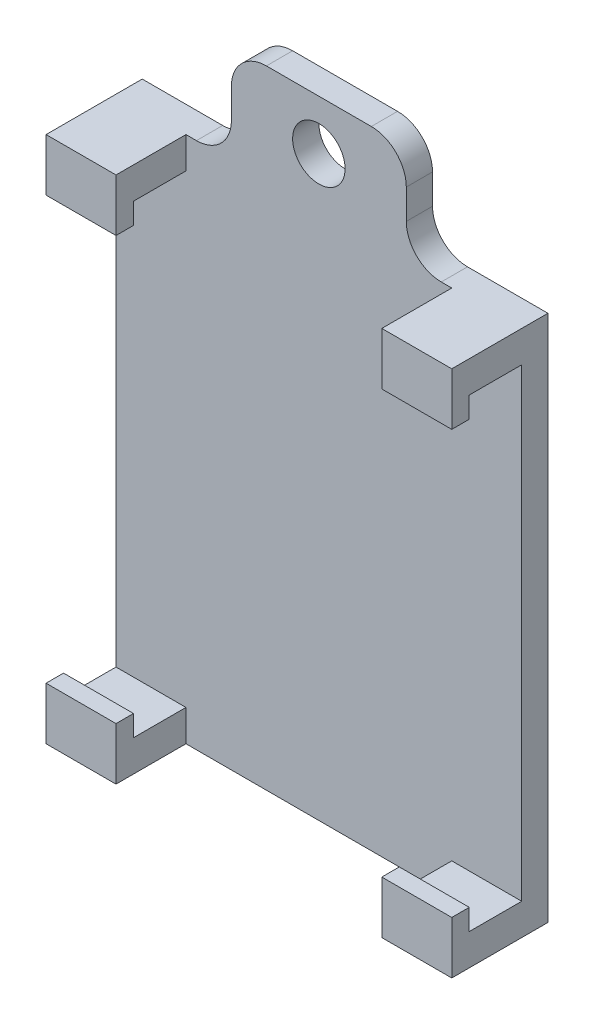
SolidWorks part; units mm, degrees
ref_plane "Front" through (0, 0, 0) normal (0, 0, 1) x (1, 0, 0)
ref_plane "Top" through (0, 0, 0) normal (0, 1, 0) x (1, 0, 0)
ref_plane "Right" through (0, 0, 0) normal (1, 0, 0) x (0, 0, -1)
sketch "Sketch1" plane through (0, 0, 0) normal (0, 1, 0) x (1, 0, 0)
  line L1 (0, 0) -> (23.2, 0)
  line L2 (0, 0) -> (0, 41.57)
  line L3 (0, 41.57) -> (23.2, 41.57)
  line L4 (23.2, 0) -> (23.2, 41.57)
  dimension "D1" = 23.2
  dimension "D2" = 41.57
extrude "Boss-Extrude1" add sketch "Sketch1" along normal blind 1.5
sketch "Sketch2" plane through (0, 1.5, 0) normal (0, 1, 0) x (1, 0, 0)
  line L0 (0, 41.57) -> (0, 0) construction
  line L1 (0, 32.87) -> (23.2, 32.87)
  line L2 (0, 32.87) -> (0, 35.87)
  line L3 (0, 35.87) -> (23.2, 35.87)
  line L4 (23.2, 32.87) -> (23.2, 35.87)
  line L5 (23.2, 0) -> (23.2, 41.57) construction
  line L7 (0, 8.7) -> (23.2, 8.7)
  line L8 (0, 8.7) -> (0, 5.7)
  line L9 (0, 5.7) -> (23.2, 5.7)
  line L10 (23.2, 8.7) -> (23.2, 5.7)
  line L11 (11.6, 8.7) -> (11.6, 32.87) construction
  point P14 (0, 20.785)
  point P15 (11.6, 20.785)
  dimension "D2" = 3
  dimension "D3" = 3
  dimension "D1" = 24.17
extrude "Boss-Extrude2" add sketch "Sketch2" along normal blind 4
sketch "Sketch3" plane through (0, 0, -32.87) normal (0, 0, 1) x (1, 0, 0)
  line L0 (23.2, 5.5) -> (23.2, 1.5) construction
  line L1 (0, 1.5) -> (23.2, 1.5)
  line L2 (0, 1.5) -> (0, 4.5)
  line L3 (0, 4.5) -> (23.2, 4.5)
  line L4 (23.2, 1.5) -> (23.2, 4.5)
  dimension "D1" = 3
extrude "Cut-Extrude1" cut sketch "Sketch3" against normal blind 1.2
sketch "Sketch4" plane through (0, 0, -8.7) normal (0, 0, -1) x (-1, 0, 0)
  line L0 (0, 5.5) -> (0, 1.5) construction
  line L1 (-23.2, 1.5) -> (0, 1.5)
  line L2 (-23.2, 1.5) -> (-23.2, 4.5)
  line L3 (-23.2, 4.5) -> (0, 4.5)
  line L4 (0, 1.5) -> (0, 4.5)
  dimension "D1" = 3
extrude "Cut-Extrude2" cut sketch "Sketch4" against normal blind 1.2
sketch "Sketch5" plane through (0, 1.5, 0) normal (0, 1, 0) x (1, 0, 0)
  line L0 (0, 41.57) -> (0, 35.87) construction
  line L1 (23.2, 41.57) -> (0, 41.57) construction
  line L2 (0, 5.7) -> (0, 0) construction
  circle A0 centre (11.6, 38.72) radius 1.5
  circle A1 centre (11.6, 2.85) radius 1.5
  point P6 (0, 38.72)
  point P9 (11.6, 41.57)
  point P12 (0, 2.85)
  dimension "D1" = 3
  dimension "D2" = 3
extrude "Cut-Extrude3" cut sketch "Sketch5" against normal through all
sketch "Sketch6" plane through (0, 0, 0) normal (0, -1, 0) x (1, 0, 0)
  line L0 (11.6, -38.72) -> (11.6, -5.7)
  line L1 (0, -5.7) -> (23.2, -5.7) construction
sketch "Sketch7" plane through (0, 0, 0) normal (0, 1, 0) x (1, 0, 0)
  line L1 (0, 5.7) -> (23.2, 5.7)
  line L2 (0, 5.7) -> (0, 0)
  line L3 (0, 0) -> (23.2, 0)
  line L4 (23.2, 5.7) -> (23.2, 0)
extrude "Cut-Extrude4" cut sketch "Sketch7" along normal through all
sketch "Sketch8" plane through (0, 0, -5.7) normal (0, 0, 1) x (1, 0, 0)
  line L0 (0, 5.5) -> (23.2, 5.5) construction
  line L1 (4, 5.5) -> (19.2, 5.5)
  line L2 (4, 5.5) -> (4, 1.5)
  line L3 (4, 1.5) -> (19.2, 1.5)
  line L4 (19.2, 5.5) -> (19.2, 1.5)
  line L5 (0, 1.5) -> (23.2, 1.5) construction
  line L6 (0, 1.5) -> (4, 1.5) construction
  line L16 (0, 5.5) -> (0, 0) construction
  point P8 (11.6, 5.5)
  point P9 (11.6, 5.5)
  dimension "D1" = 4
extrude "Cut-Extrude5" cut sketch "Sketch8" against normal through all
sketch "Sketch9" plane through (0, 1.5, 0) normal (0, 1, 0) x (1, 0, 0)
  line L0 (4, 35.87) -> (0, 35.87) construction
  line L1 (0, 41.57) -> (6.6, 41.57)
  line L2 (0, 41.57) -> (0, 35.87)
  line L3 (0, 35.87) -> (6.6, 35.87)
  line L4 (6.6, 41.57) -> (6.6, 35.87)
  line L5 (11.6, 41.57) -> (11.6, 5.7) construction
  line L6 (23.2, 41.57) -> (0, 41.57) construction
  line L7 (4, 5.7) -> (19.2, 5.7) construction
  line L8 (16.6, 41.57) -> (16.6, 35.87)
  line L9 (23.2, 35.87) -> (16.6, 35.87)
  line L10 (23.2, 41.57) -> (23.2, 35.87)
  line L11 (23.2, 41.57) -> (16.6, 41.57)
  dimension "D1" = 5
extrude "Cut-Extrude6" cut sketch "Sketch9" against normal through all
fillet "Fillet1" radius 2 4 edges at (6.6, 0.75, -35.87) (6.6, 0.75, -41.57) (16.6, 0.75, -41.57) (16.6, 0.75, -35.87)
move or copy body "Body-Move/Copy1" bodies to move or copy 109 copy no rotation origin (0, 2.75, -20.7) rotation axis (1, 0, 0) rotation angle 90
equation "\"Board Length\"= 26.57'The dimension of the board parallel with the clips"
equation "\"Board Width\"= 23.2'The dimension of the board perpendicular to the clips"
equation "\"D1@Sketch1\"=\"Board Width\""
equation "\"Board Slot Length\"= \"Board Length\" - 2 * \"Overhang Cut\""
equation "\"Overhang Cut\"= 1.2"
equation "\"D1@Cut-Extrude1\"=\"Overhang Cut\""
equation "\"D1@Sketch2\"=\"Board Slot Length\""
equation "\"Mount Length\"= \"Board Length\" + 7.5 * 2"
equation "\"D2@Sketch1\"=\"Mount Length\""
